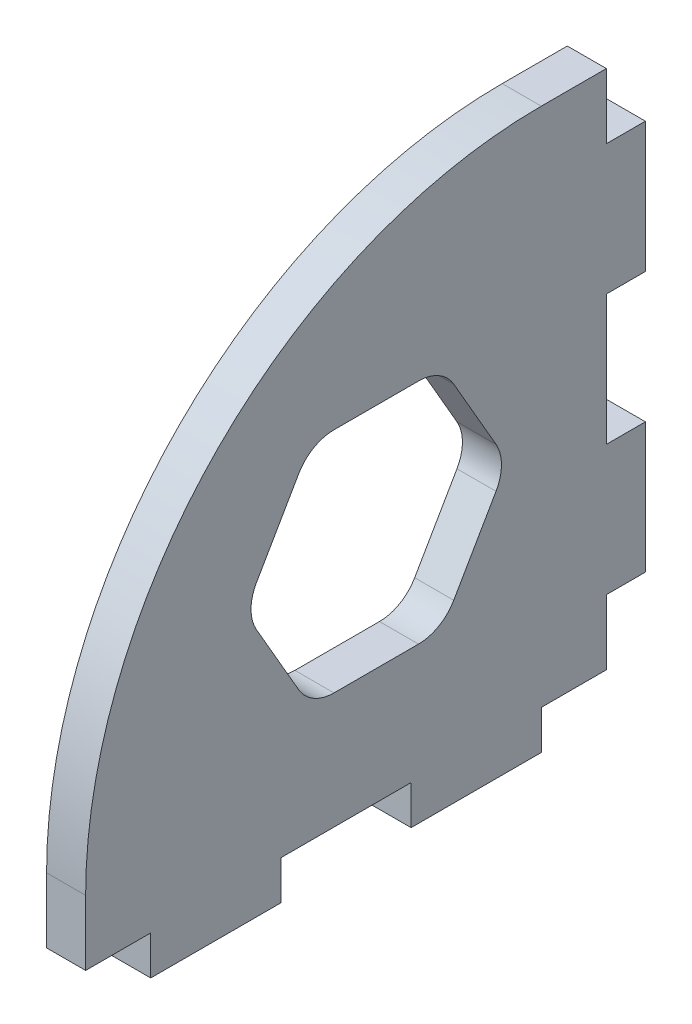
SolidWorks part; units mm, degrees
material "Pine"
ref_plane "Front Plane" through (0, 0, 0) normal (0, 0, 1) x (1, 0, 0)
ref_plane "Top Plane" through (0, 0, 0) normal (0, 1, 0) x (1, 0, 0)
ref_plane "Right Plane" through (0, 0, 0) normal (1, 0, 0) x (0, 0, -1)
sketch "Sketch1" plane through (0, 0, 0) normal (1, 0, 0) x (0, 0, -1)
  line L0 (0, 0) -> (-5, 0)
  line L1 (-5, 0) -> (-5, -3)
  line L2 (-5, -3) -> (-15, -3)
  line L3 (-15, -3) -> (-15, 0)
  line L4 (-15, 0) -> (-25, 0)
  line L5 (-25, 0) -> (-25, -3)
  line L6 (-25, -3) -> (-35, -3)
  line L7 (-35, -3) -> (-35, 0)
  line L8 (-35, 0) -> (-40, 0)
  line L9 (-40, 0) -> (-40, 5)
  line L10 (-40, 40) -> (0, 0) construction
  line L11 (0, 40) -> (-5, 40)
  line L12 (0, 35) -> (0, 40)
  line L13 (3, 35) -> (0, 35)
  line L14 (3, 25) -> (3, 35)
  line L15 (0, 25) -> (3, 25)
  line L16 (0, 15) -> (0, 25)
  line L17 (3, 15) -> (0, 15)
  line L18 (3, 5) -> (3, 15)
  line L19 (0, 5) -> (3, 5)
  line L20 (0, 0) -> (0, 5)
  line L22 (-8.4761, 19.2402) -> (-11.7237, 24.8652)
  line L23 (-14.4301, 26.4277) -> (-20.9253, 26.4277)
  line L24 (-23.6316, 24.8652) -> (-26.8792, 19.2402)
  line L25 (-26.8792, 16.1152) -> (-23.6316, 10.4902)
  line L26 (-20.9253, 8.9277) -> (-14.4301, 8.9277)
  line L27 (-11.7237, 10.4902) -> (-8.4761, 16.1152)
  arc A0 (-40, 5) -> (-5, 40) centre (-5, 5) cw
  circle A1 centre (-17.6777, 17.6777) radius 8.75 construction
  arc A2 (-14.4301, 8.9277) -> (-11.7237, 10.4902) centre (-14.4301, 12.0527) ccw
  arc A3 (-23.6316, 10.4902) -> (-20.9253, 8.9277) centre (-20.9253, 12.0527) ccw
  arc A4 (-26.8792, 19.2402) -> (-26.8792, 16.1152) centre (-24.1729, 17.6777) ccw
  arc A5 (-20.9253, 26.4277) -> (-23.6316, 24.8652) centre (-20.9253, 23.3027) ccw
  arc A6 (-11.7237, 24.8652) -> (-14.4301, 26.4277) centre (-14.4301, 23.3027) ccw
  arc A7 (-8.4761, 19.2402) -> (-8.4761, 16.1152) centre (-11.1825, 17.6777) cw
  dimension "D4" = 35
  dimension "D6" = 17.5
  dimension "D7" = 3.125
  dimension "D1" = 45
  dimension "D2" = 5
  dimension "D3" = 10
  dimension "D5" = 3
  dimension "D8" = 25
extrude "Boss-Extrude1" add sketch "Sketch1" along normal mid plane 3
